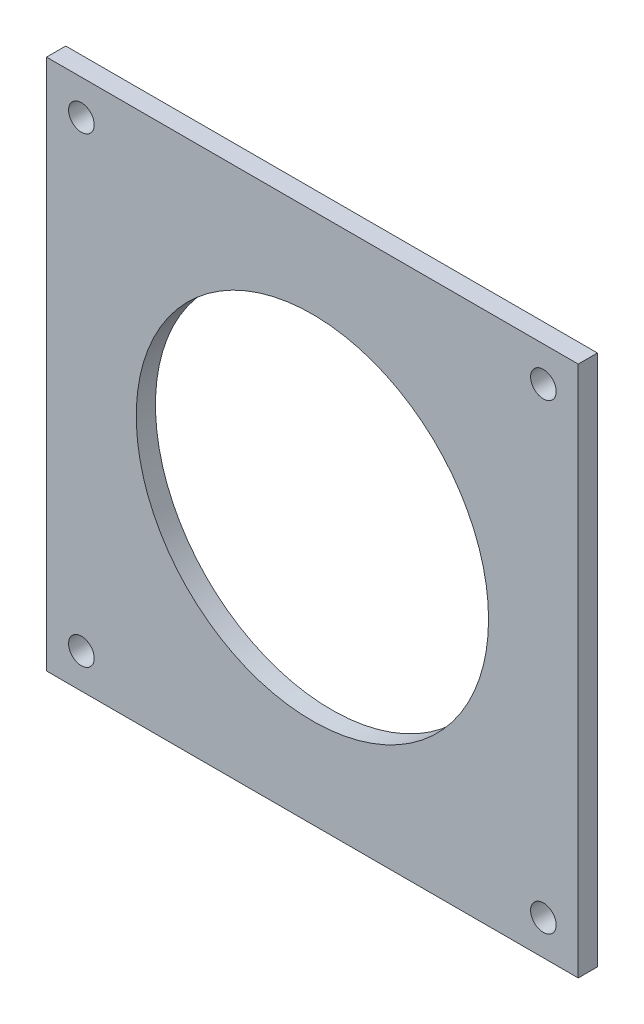
SolidWorks part; units mm, degrees
ref_plane "Front Plane" through (0, 0, 0) normal (1, 0, 0) x (0, 1, 0)
ref_plane "Top Plane" through (0, 0, 0) normal (0, 0, 1) x (0, 1, 0)
ref_plane "Right Plane" through (0, 0, 0) normal (0, 1, 0) x (-1, 0, 0)
sketch "Sketch1" plane through (0, 0, 0) normal (0, 0, 1) x (0, 1, 0)
  line L0 (-41.5, -41.5) -> (41.5, -41.5)
  line L1 (41.5, -41.5) -> (41.5, 41.5)
  line L2 (41.5, 41.5) -> (-41.5, 41.5)
  line L3 (-41.5, 41.5) -> (-41.5, -41.5)
  circle A0 centre (36.0624, -36.0624) radius 2
  circle A1 centre (-36.0624, -36.0624) radius 2
  circle A2 centre (0, 0) radius 27.5
  circle A3 centre (36.0624, 36.0624) radius 2
  circle A4 centre (-36.0624, 36.0624) radius 2
extrude "Boss-Extrude1" add sketch "Sketch1" along normal blind 3
